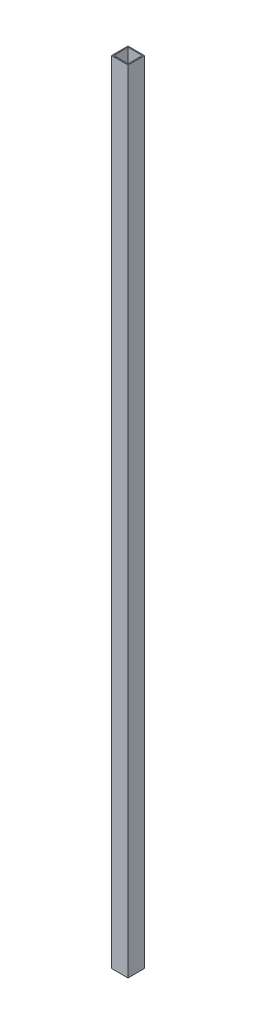
SolidWorks part; units mm, degrees
ref_plane "Front Plane" through (0, 0, 0) normal (0, 0, 1) x (1, 0, 0)
ref_plane "Top Plane" through (0, 0, 0) normal (0, 1, 0) x (1, 0, 0)
ref_plane "Right Plane" through (0, 0, 0) normal (1, 0, 0) x (0, 0, -1)
sketch "Sketch1" plane through (0, 0, 0) normal (0, 1, 0) x (1, 0, 0)
  line L1 (-25.4, 25.4) -> (25.4, 25.4)
  line L2 (-25.4, 25.4) -> (-25.4, -25.4)
  line L3 (-25.4, -25.4) -> (25.4, -25.4)
  line L4 (25.4, 25.4) -> (25.4, -25.4)
  line L5 (-25.4, 25.4) -> (25.4, -25.4) construction
  line L6 (-25.4, -25.4) -> (25.4, 25.4) construction
  line L7 (-22.225, 22.225) -> (22.225, 22.225)
  line L8 (-22.225, 22.225) -> (-22.225, -22.225)
  line L9 (-22.225, -22.225) -> (22.225, -22.225)
  line L10 (22.225, 22.225) -> (22.225, -22.225)
  line L11 (-22.225, 22.225) -> (22.225, -22.225) construction
  line L12 (-22.225, -22.225) -> (22.225, 22.225) construction
  point P0 (0, 0)
  point P6 (0, 0)
  dimension "D1" = 50.8
  dimension "D2" = 50.8
  dimension "D3" = 3.175
extrude "Boss-Extrude1" add sketch "Sketch1" along normal blind 2438.4
